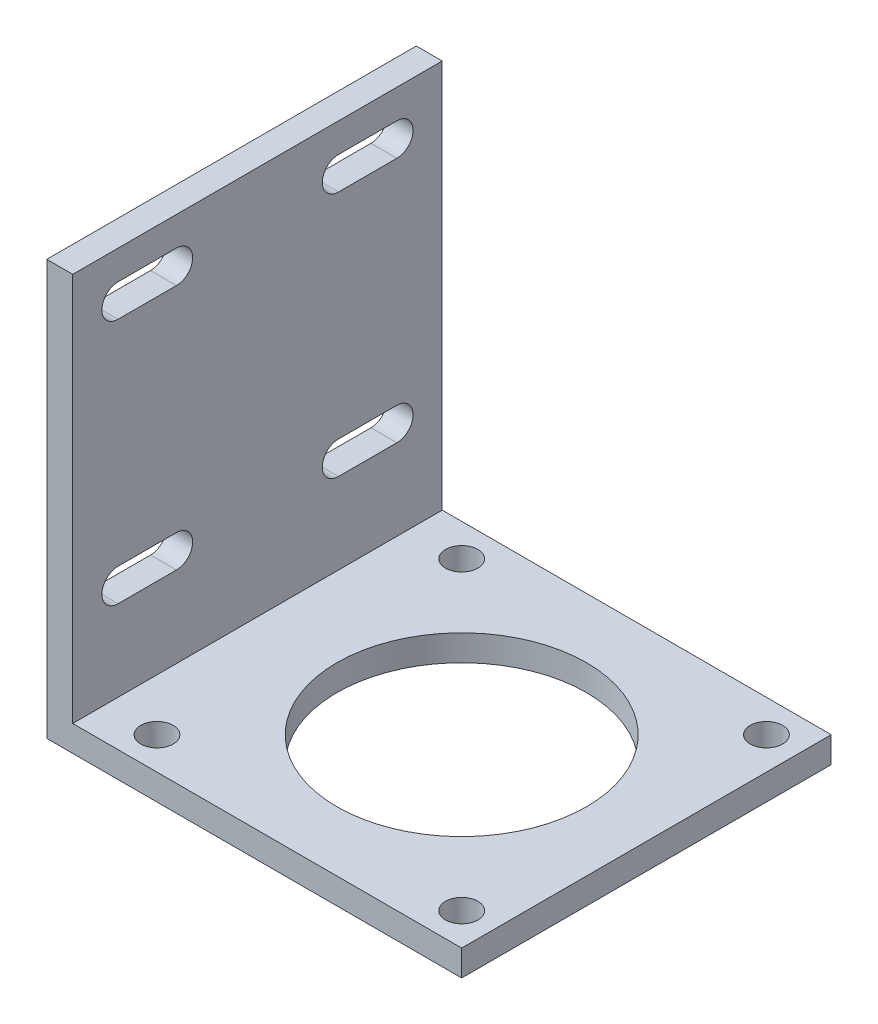
SolidWorks part; units mm, degrees
ref_plane "Front Plane" through (0, 0, 0) normal (0, 0, 1) x (1, 0, 0)
ref_plane "Top Plane" through (0, 0, 0) normal (0, 1, 0) x (1, 0, 0)
ref_plane "Right Plane" through (0, 0, 0) normal (1, 0, 0) x (0, 0, -1)
sketch "Sketch1" plane through (0, 0, 0) normal (0, 1, 0) x (1, 0, 0)
  line L1 (-32, 28.5) -> (32, 28.5)
  line L2 (-32, 28.5) -> (-32, -28.5)
  line L3 (-32, -28.5) -> (32, -28.5)
  line L4 (32, 28.5) -> (32, -28.5)
  line L5 (-32, 28.5) -> (32, -28.5) construction
  line L6 (-32, -28.5) -> (32, 28.5) construction
  point P0 (0, 0)
  dimension "D1" = 64
  dimension "D2" = 57
extrude "Boss-Extrude1" add sketch "Sketch1" along normal blind 4
sketch "Sketch2" plane through (0, 4, 0) normal (0, 1, 0) x (1, 0, 0)
  line L0 (-32, -28.5) -> (32, -28.5) construction
  line L1 (-32, 28.5) -> (-28, 28.5)
  line L2 (-32, 28.5) -> (-32, -28.5)
  line L3 (-32, -28.5) -> (-28, -28.5)
  line L4 (-28, 28.5) -> (-28, -28.5)
  dimension "D1" = 4
extrude "Boss-Extrude2" add sketch "Sketch2" along normal blind 60
sketch "Sketch3" plane through (0, 0, 0) normal (0, -1, 0) x (1, 0, 0)
  line L1 (32, 28.5) -> (32, -28.5) construction
  circle A0 centre (3.5, 0) radius 19.25
  dimension "D1" = 38.5
  dimension "D2" = 28.5
extrude "Cut-Extrude1" cut sketch "Sketch3" against normal blind 60
hole_wizard "Ø5.0 (5) Diameter Hole1" positions "Sketch5" profile "Sketch4" hole size "Ø5.0" standard "ISO" end condition through all
sketch "Sketch5" plane through (0, 0, 0) normal (0, -1, 0) x (-1, 0, 0)
  line L1 (32, -28.5) -> (-32, -28.5) construction
  line L3 (-32, -28.5) -> (-32, 28.5) construction
  point P0 (-27, -23.5)
  point P2 (-27, 23.5)
  point P4 (20, 23.5)
  point P6 (20, -23.5)
  dimension "D1" = 47
  dimension "D2" = 47
  dimension "D3" = 47
  dimension "D4" = 47
  dimension "D5" = 5
  dimension "D6" = 5
  dimension "D7" = 5
sketch "Sketch4" plane through (27, 0, 23.5) normal (1, 0, 0) x (0, 0, -1)
  line L0 (0, 0) -> (0, 64)
  line L1 (0, 64) -> (2.5, 64)
  line L2 (2.5, 64) -> (2.5, 0)
  line L5 (2.5, 0) -> (0, 0)
  line L11 (0, -6.35) -> (0, 107.95) construction
  dimension "Thru Hole Dia." = 5
  dimension "Thru Hole Depth" = 64
sketch "Sketch6" plane through (-32, 0, 0) normal (-1, 0, 0) x (0, 0, 1)
  line L0 (-21.5, 16.5) -> (-12.5, 16.5)
  line L1 (-21.5, 21.5) -> (-12.5, 21.5)
  line L2 (-28.5, 0) -> (28.5, 0) construction
  line L3 (-28.5, 64) -> (-28.5, 0) construction
  line L4 (12.5, 16.5) -> (21.5, 16.5)
  line L5 (12.5, 21.5) -> (21.5, 21.5)
  line L6 (28.5, 64) -> (28.5, 0) construction
  line L7 (-21.5, 54.5) -> (-12.5, 54.5)
  line L8 (-21.5, 59.5) -> (-12.5, 59.5)
  line L9 (-28.5, 64) -> (28.5, 64) construction
  line L10 (12.5, 54.5) -> (21.5, 54.5)
  line L11 (12.5, 59.5) -> (21.5, 59.5)
  arc A0 (-21.5, 16.5) -> (-21.5, 21.5) centre (-21.5, 19) cw
  arc A1 (-12.5, 16.5) -> (-12.5, 21.5) centre (-12.5, 19) ccw
  arc A2 (12.5, 16.5) -> (12.5, 21.5) centre (12.5, 19) cw
  arc A3 (21.5, 16.5) -> (21.5, 21.5) centre (21.5, 19) ccw
  arc A4 (-21.5, 54.5) -> (-21.5, 59.5) centre (-21.5, 57) cw
  arc A5 (-12.5, 54.5) -> (-12.5, 59.5) centre (-12.5, 57) ccw
  arc A6 (12.5, 54.5) -> (12.5, 59.5) centre (12.5, 57) cw
  arc A7 (21.5, 54.5) -> (21.5, 59.5) centre (21.5, 57) ccw
  dimension "D1" = 2.5
  dimension "D5" = 9
  dimension "D7" = 2.5
  dimension "D11" = 2.5
  dimension "D14" = 9
  dimension "D2" = 9
  dimension "D3" = 19
  dimension "D4" = 7
  dimension "D6" = 7
  dimension "D8" = 9
  dimension "D9" = 7
  dimension "D10" = 7
  dimension "D12" = 7
  dimension "D13" = 7
extrude "Cut-Extrude2" cut sketch "Sketch6" against normal blind 60
